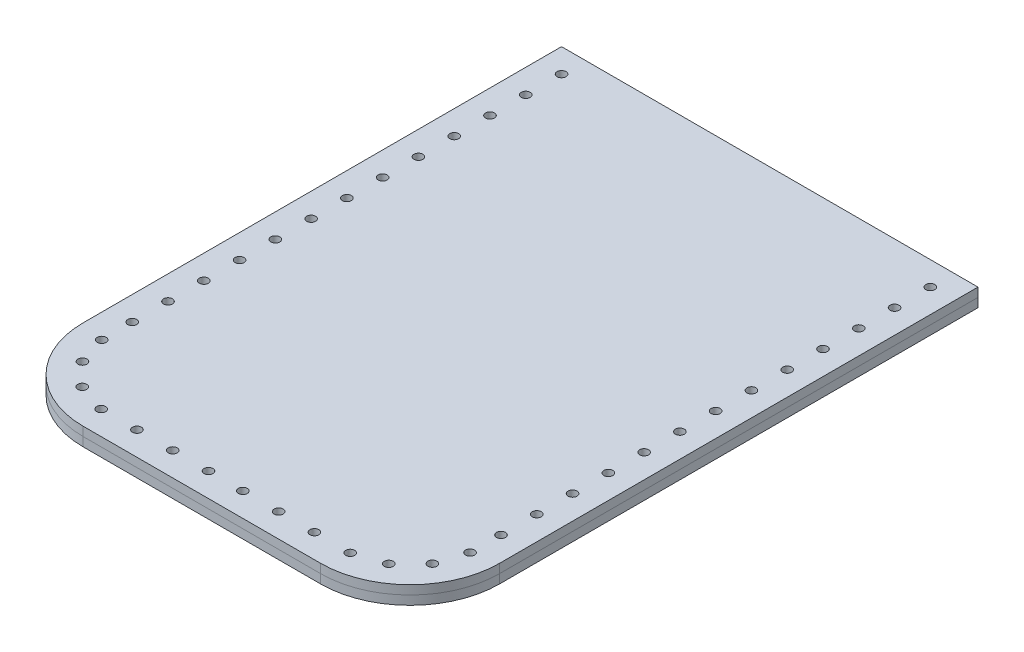
SolidWorks part; units mm, degrees
ref_plane "Front Plane" through (0, 0, 0) normal (0, 0, 1) x (1, 0, 0)
ref_plane "Top Plane" through (0, 0, 0) normal (0, 1, 0) x (1, 0, 0)
ref_plane "Right Plane" through (0, 0, 0) normal (1, 0, 0) x (0, 0, -1)
sketch "Sketch1" plane through (0, 0, 0) normal (0, 1, 0) x (1, 0, 0)
  line L1 (-19.925, -47.625) -> (19.925, -47.625)
  line L2 (-34.925, -32.625) -> (-34.925, 47.625)
  line L3 (-34.925, 47.625) -> (34.925, 47.625)
  line L4 (34.925, -32.625) -> (34.925, 47.625)
  line L5 (-34.925, -47.625) -> (34.925, 47.625) construction
  line L6 (-34.925, 47.625) -> (34.925, -47.625) construction
  arc A0 (19.925, -47.625) -> (34.925, -32.625) centre (19.925, -32.625) ccw
  arc A1 (-19.925, -47.625) -> (-34.925, -32.625) centre (-19.925, -32.625) cw
  point P0 (0, 0)
  dimension "D3" = 15
  dimension "D1" = 69.85
  dimension "D2" = 95.25
extrude "front panel" add sketch "Sketch1" along normal blind 1.5
sketch "front label" plane through (0, 1.5, 0) normal (0, 1, 0) x (1, 0, 0)
  text T0 "Front - outside"
sketch "Sketch3" plane through (0, 0, 0) normal (0, -1, 0) x (1, 0, 0)
  line L0 (34.925, -47.625) -> (-34.925, -47.625) construction
  line L1 (-34.925, -47.625) -> (-34.925, 32.625) construction
  line L2 (-19.925, 47.625) -> (19.925, 47.625) construction
  line L3 (34.925, 32.625) -> (34.925, -47.625) construction
  line L4 (34.925, -47.625) -> (28.575, -47.625)
  line L5 (-34.925, -47.625) -> (-34.925, 32.625)
  line L6 (-19.925, 47.625) -> (19.925, 47.625)
  line L7 (34.925, 32.625) -> (34.925, -47.625)
  line L8 (28.575, -47.625) -> (0, -19.05)
  line L9 (0, -19.05) -> (-28.575, -47.625)
  line L10 (-28.575, -47.625) -> (-34.925, -47.625)
  arc A0 (-19.925, 47.625) -> (-34.925, 32.625) centre (-19.925, 32.625) ccw construction
  arc A1 (34.925, 32.625) -> (19.925, 47.625) centre (19.925, 32.625) ccw construction
  arc A2 (-19.925, 47.625) -> (-34.925, 32.625) centre (-19.925, 32.625) ccw
  arc A3 (34.925, 32.625) -> (19.925, 47.625) centre (19.925, 32.625) ccw
  dimension "D1" = 6.35
  dimension "D2" = 66.675
extrude "back panel" add sketch "Sketch3" along normal blind 1.5 separate body
sketch "back label" plane through (0, -1.5, 0) normal (0, -1, 0) x (1, 0, 0)
  text T0 "Rear - outside"
sketch "Sketch5" plane through (0, 1.5, 0) normal (0, 1, 0) x (1, 0, 0)
  line L9 (34.925, 47.625) -> (-34.925, 47.625) construction
  line L10 (0, -43.625) -> (0, -38.592) construction
  line L12 (30.925, -32.625) -> (30.925, 47.625)
  line L13 (-19.925, -43.625) -> (19.925, -43.625)
  line L14 (-30.925, 47.625) -> (-30.925, -32.625)
  line L15 (30.925, -32.625) -> (30.925, 47.625) construction
  line L16 (-19.925, -43.625) -> (19.925, -43.625) construction
  line L17 (-30.925, 47.625) -> (-30.925, -32.625) construction
  circle A6 centre (-30.925, 43.625) radius 0.75
  circle A7 centre (-30.925, 37.625) radius 0.75
  arc A8 (19.925, -43.625) -> (30.925, -32.625) centre (19.925, -32.625) ccw
  arc A9 (-30.925, -32.625) -> (-19.925, -43.625) centre (-19.925, -32.625) ccw
  arc A10 (19.925, -43.625) -> (30.925, -32.625) centre (19.925, -32.625) ccw construction
  arc A11 (-30.925, -32.625) -> (-19.925, -43.625) centre (-19.925, -32.625) ccw construction
  circle A12 centre (-30.925, 31.625) radius 0.75
  circle A13 centre (-30.925, 25.625) radius 0.75
  circle A14 centre (-30.925, 19.625) radius 0.75
  circle A15 centre (-30.925, 13.625) radius 0.75
  circle A16 centre (-30.925, 7.625) radius 0.75
  circle A17 centre (-30.925, 1.625) radius 0.75
  circle A18 centre (-30.925, -4.375) radius 0.75
  circle A19 centre (-30.925, -10.375) radius 0.75
  circle A20 centre (-30.925, -16.375) radius 0.75
  circle A21 centre (-30.925, -22.375) radius 0.75
  circle A22 centre (-30.925, -28.375) radius 0.75
  circle A23 centre (-30.8877, -33.53) radius 0.75
  circle A24 centre (-29.3473, -38.3014) radius 0.75
  circle A25 centre (-25.7058, -41.9835) radius 0.75
  circle A27 centre (-2.8828, -43.625) radius 0.75
  circle A28 centre (-8.8828, -43.625) radius 0.75
  circle A29 centre (-14.8828, -43.625) radius 0.75
  circle A30 centre (-20.8828, -43.625) radius 0.75
  arc A31 (30.925, -32.625) -> (19.925, -43.625) centre (19.925, -32.625) cw construction
  arc A32 (-19.925, -43.625) -> (-30.925, -32.625) centre (-19.925, -32.625) cw construction
  circle A33 centre (20.8828, -43.625) radius 0.75
  circle A34 centre (14.8828, -43.625) radius 0.75
  circle A35 centre (8.8828, -43.625) radius 0.75
  circle A36 centre (2.8828, -43.625) radius 0.75
  circle A37 centre (25.7058, -41.9835) radius 0.75
  circle A38 centre (29.3473, -38.3014) radius 0.75
  circle A39 centre (30.8877, -33.53) radius 0.75
  circle A40 centre (30.925, -28.375) radius 0.75
  circle A41 centre (30.925, -22.375) radius 0.75
  circle A42 centre (30.925, -16.375) radius 0.75
  circle A43 centre (30.925, -10.375) radius 0.75
  circle A44 centre (30.925, -4.375) radius 0.75
  circle A45 centre (30.925, 1.625) radius 0.75
  circle A46 centre (30.925, 7.625) radius 0.75
  circle A47 centre (30.925, 13.625) radius 0.75
  circle A48 centre (30.925, 19.625) radius 0.75
  circle A49 centre (30.925, 25.625) radius 0.75
  circle A50 centre (30.925, 31.625) radius 0.75
  circle A51 centre (30.925, 37.625) radius 0.75
  circle A52 centre (30.925, 43.625) radius 0.75
  point P45 (-25.4555, -42.1336)
  point P46 (-29.3473, -38.3014)
  point P53 (-25.7058, -41.9835)
  point P54 (-30.925, -33.53)
  dimension "D2" = 1.5
  dimension "D3" = 4
  dimension "D5" = 4
  dimension "D1" = 4
  dimension "D4" = 13
extrude "Cut-Extrude1" cut sketch "Sketch5" against normal through all both and the other way through all
